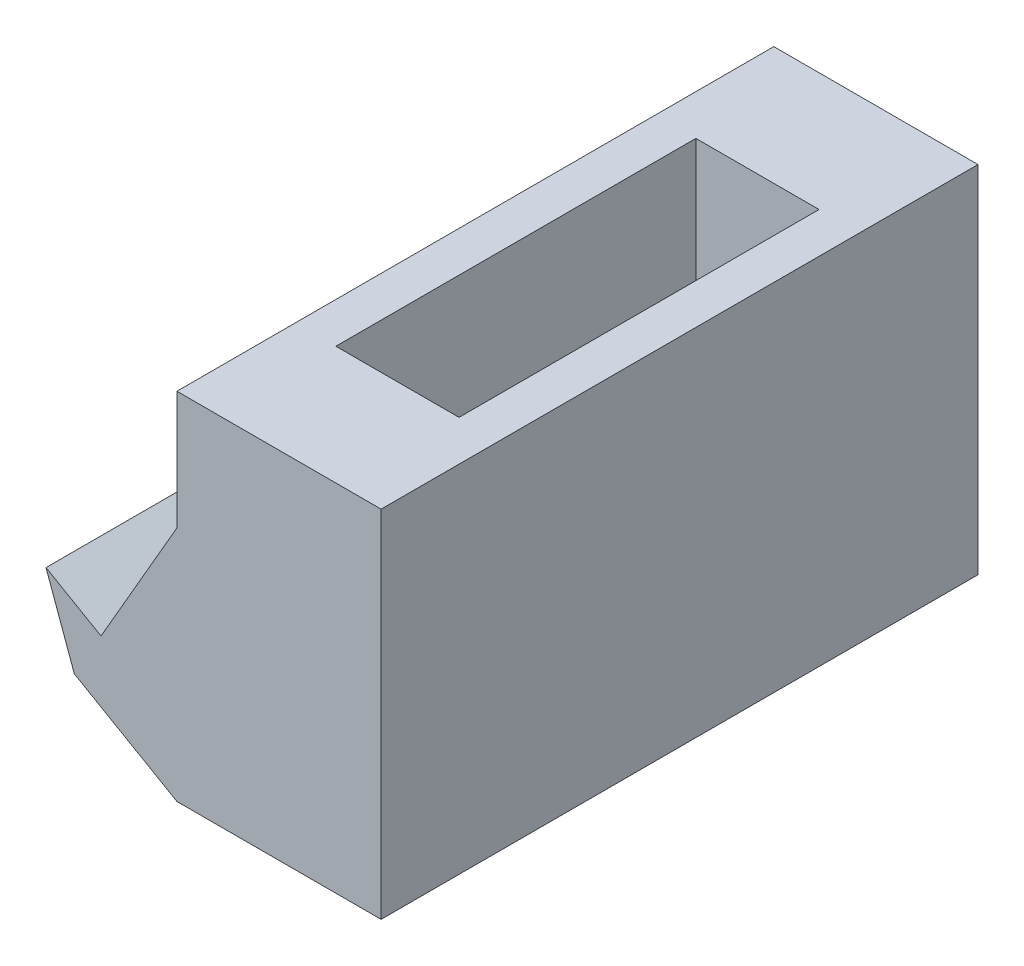
SolidWorks part; units mm, degrees
ref_plane "Front Plane" through (0, 0, 0) normal (0, 0, 1) x (1, 0, 0)
ref_plane "Top Plane" through (0, 0, 0) normal (0, 1, 0) x (1, 0, 0)
ref_plane "Right Plane" through (0, 0, 0) normal (1, 0, 0) x (0, 0, -1)
sketch "草图1" plane through (0, 0, 0) normal (0, 1, 0) x (1, 0, 0)
  line L1 (-4.3105, 12.6) -> (4.3105, 12.6)
  line L2 (-4.3105, 12.6) -> (-4.3105, -12.6)
  line L3 (-4.3105, -12.6) -> (4.3105, -12.6)
  line L4 (4.3105, 12.6) -> (4.3105, -12.6)
  line L5 (-4.3105, 12.6) -> (4.3105, -12.6) construction
  line L6 (-4.3105, -12.6) -> (4.3105, 12.6) construction
  line L7 (-2.6, 7.6) -> (2.6, 7.6)
  line L8 (-2.6, 7.6) -> (-2.6, -7.6)
  line L9 (-2.6, -7.6) -> (2.6, -7.6)
  line L10 (2.6, 7.6) -> (2.6, -7.6)
  line L11 (-2.6, 7.6) -> (2.6, -7.6) construction
  line L12 (-2.6, -7.6) -> (2.6, 7.6) construction
  point P0 (0, 0)
  point P6 (0, 0)
  dimension "D1" = 15.2
  dimension "D2" = 5.2
  dimension "D3" = 5
extrude "凸台-拉伸1" add sketch "草图1" along normal blind 5 and the other way blind 10
sketch "草图2" plane through (0, 0, 12.6) normal (0, 0, 1) x (1, 0, 0)
  line L0 (-4.3105, -10) -> (-4.3105, 5) construction
  line L1 (-4.3105, 0) -> (-4.3105, -10)
  line L2 (-4.3105, 0) -> (-7.5158, -5.5517)
  line L3 (-8.6407, -7.5) -> (-4.3105, -10)
  line L4 (-8.6407, -7.5) -> (-9.8377, -4.2111)
  line L5 (-9.8377, -4.2111) -> (-7.5158, -5.5517)
  arc A0 (-4.3105, 0) -> (-4.3105, -10) centre (-4.3105, -5) ccw construction
  line M5 (-4.3105, 5) -> (-4.3105, -10)
  dimension "D1" = 10
  dimension "D2" = 60
  dimension "D3" = 3.5
  dimension "D4" = 50
  dimension "D5" = 40
extrude "凸台-拉伸3" add sketch "草图2" against normal up to surface (25.2 mm away) contours A0 M5 | L1 L3 L4 L5 L2
